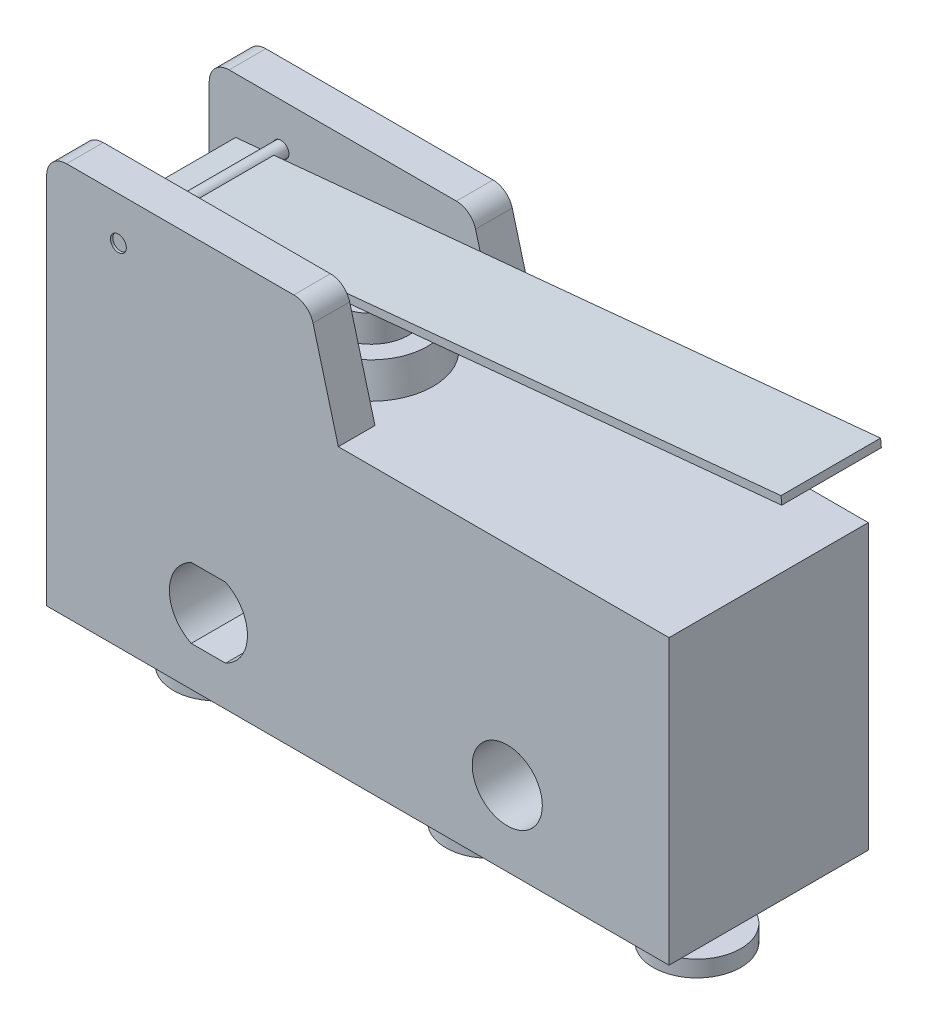
SolidWorks part; units mm, degrees
ref_plane "Front" through (0, 0, 0) normal (0, 0, 1) x (1, 0, 0)
ref_plane "Top" through (0, 0, 0) normal (0, 1, 0) x (1, 0, 0)
ref_plane "Right" through (0, 0, 0) normal (1, 0, 0) x (0, 0, -1)
sketch "Sketch1" plane through (0, 0, 0) normal (0, 0, 1) x (1, 0, 0)
  line L0 (-2.7559, 9.0424) -> (-2.7559, 0) construction
  line L1 (-9.9187, 0) -> (9.9187, 0)
  line L2 (-9.9187, 0) -> (-9.9187, 9.0424)
  line L3 (-9.9187, 9.0424) -> (9.9187, 9.0424)
  line L4 (9.9187, 0) -> (9.9187, 9.0424)
  line L5 (-5.3102, 3.5052) -> (-4.2148, 3.5052)
  line L6 (-5.3102, 1.27) -> (-4.2148, 1.27)
  line L7 (-4.7625, 2.3876) -> (4.7625, 2.3876) construction
  arc A0 (-5.3102, 3.5052) -> (-5.3102, 1.27) centre (-4.7625, 2.3876) ccw
  circle A1 centre (4.7625, 2.3876) radius 1.1176
  arc A2 (-4.2148, 1.27) -> (-4.2148, 3.5052) centre (-4.7625, 2.3876) ccw
  point P8 (-6.0071, 2.3876)
  point P15 (-3.5179, 2.3876)
  dimension "D3" = 2.4892
  dimension "D5" = 2.2352
  dimension "D6" = 5.1562
  dimension "D7" = 9.525
  dimension "D8" = 2.3876
  dimension "D9" = 7.5184
  dimension "D1" = 9.0424
  dimension "D2" = 19.8374
  dimension "D4" = 2.2352
extrude "Extrude1" add sketch "Sketch1" along normal mid plane 6.35
sketch "Sketch3" plane through (0, 0, 0) normal (0, 0, 1) x (1, 0, 0)
  line L0 (-4.7371, 9.0424) -> (-4.558, 10.0584)
  line L1 (-4.558, 10.0584) -> (-3.9497, 10.0584)
  line L2 (-3.9497, 10.0584) -> (-3.9497, 9.0424)
  line L3 (-3.9497, 9.0424) -> (-4.7371, 9.0424)
  line L4 (-3.9243, 9.5504) -> (-3.9243, 10.8966)
  line L5 (-2.7559, 9.0424) -> (-2.7559, 0) construction
  line L6 (-2.7559, 11.2776) -> (-2.7559, 9.5504)
  line L7 (-2.7559, 9.5504) -> (-3.9243, 9.5504)
  line L8 (-2.7559, 11.2776) -> (-2.7559, 11.5828) construction
  line L9 (-9.9187, 9.0424) -> (9.9187, 9.0424) construction
  line L10 (-3.9243, 10.8966) -> (-3.6191, 10.8966)
  arc A0 (-3.6191, 10.8966) -> (-2.7559, 11.2776) centre (-2.7559, 10.1092) cw
  circle A1 centre (4.7625, 2.3876) radius 1.1176 construction
  arc A2 (-5.3102, 3.5052) -> (-5.3102, 1.27) centre (-4.7625, 2.3876) ccw construction
  point P20 (-2.7559, 10.7696)
  dimension "D5" = 8.382
  dimension "D9" = 1.1684
  dimension "D1" = 3.9624
  dimension "D2" = 7.6708
  dimension "D3" = 2.3368
  dimension "D4" = 0.0254
  dimension "D6" = 0.508
  dimension "D7" = 80
  dimension "D8" = 0.381
  dimension "D10" = 0.508
revolve "Revolve1" add sketch "Sketch3" angle 360 about L8
sketch "Sketch5" plane through (0, 0, 0) normal (0, 0, 1) x (1, 0, 0)
  line L1 (-8.6487, 11.0236) -> (12.0015, 11.0236)
  line L2 (-8.6487, 11.0236) -> (-8.6487, 11.2776)
  line L3 (-8.6487, 11.2776) -> (12.0015, 11.2776)
  line L4 (12.0015, 11.0236) -> (12.0015, 11.2776)
  line L7 (-9.9187, 9.0424) -> (-0.6223, 9.0424) construction
  line L8 (-9.9187, 9.0424) -> (-9.9187, 12.5222) construction
  line L9 (-9.9187, 12.5222) -> (-0.6223, 12.5222) construction
  line L10 (-0.6223, 9.0424) -> (-0.6223, 12.5222) construction
  circle A1 centre (4.7625, 2.3876) radius 1.1176 construction
  arc A3 (-5.3102, 3.5052) -> (-5.3102, 1.27) centre (-4.7625, 2.3876) ccw construction
  dimension "D1" = 7.239
  dimension "D2" = 8.636
  dimension "D5" = 10.1346
  dimension "D6" = 9.2964
  dimension "D8" = 1.27
extrude "Extrude2" add sketch "Sketch5" along normal mid plane 3.175
sketch "Sketch6" plane through (0, 0, 3.175) normal (0, 0, 1) x (1, 0, 0)
  line L0 (-9.9187, 9.0424) -> (-9.9187, 11.8872)
  line L1 (-9.2837, 12.5222) -> (-2.042, 12.5222)
  line L2 (-1.4286, 12.0516) -> (-0.6223, 9.0424)
  line L3 (-0.6223, 9.0424) -> (-9.9187, 9.0424)
  line L4 (-9.9187, 9.0424) -> (-9.9187, 12.5222) construction
  line L5 (-9.9187, 12.5222) -> (-0.6223, 12.5222) construction
  line L6 (-9.9187, 9.0424) -> (9.9187, 9.0424) construction
  line L7 (-0.6223, 9.0424) -> (-0.6223, 12.5222) construction
  line L8 (-7.6327, 11.0236) -> (-7.6327, 11.2776) construction
  line L9 (-8.6487, 11.0236) -> (12.0015, 11.0236) construction
  line L10 (-8.6487, 11.2776) -> (12.0015, 11.2776) construction
  arc A0 (-9.9187, 11.8872) -> (-9.2837, 12.5222) centre (-9.2837, 11.8872) cw
  arc A1 (-2.042, 12.5222) -> (-1.4286, 12.0516) centre (-2.042, 11.8872) cw
  circle A2 centre (-7.6327, 11.1506) radius 0.254
  dimension "D2" = 0.635
  dimension "D3" = 2.286
  dimension "D4" = 0.508
  dimension "D1" = 15
extrude "Extrude3" add sketch "Sketch6" against normal blind 1.1684
mirror "Mirror1" about plane through (0, 0, 0) normal (0, 0, 1) of "Extrude3"
sketch "Sketch7" plane through (0, 0, 0) normal (0, 0, 1) x (1, 0, 0)
  circle A0 centre (-7.6327, 11.1506) radius 0.2413
  circle A1 centre (-7.6327, 11.1506) radius 0.254 construction
  dimension "D1" = 0.4826
extrude "Extrude4" add sketch "Sketch7" along normal mid plane 6.223
sketch "Sketch4" plane through (0, 0, 0) normal (0, 0, 1) x (1, 0, 0)
  line L0 (6.9977, -0.381) -> (6.9977, -1.5748)
  line L1 (6.9977, -1.5748) -> (6.2357, -1.5748)
  line L2 (6.2357, -1.5748) -> (6.2357, -2.0954)
  line L3 (6.2357, -2.0954) -> (6.6167, -2.3622)
  line L4 (6.6167, -2.3622) -> (7.6327, -2.3622)
  line L5 (7.6327, -2.3622) -> (7.6327, 0)
  line L6 (7.6327, 0) -> (6.6167, 0)
  line L7 (7.6327, 0) -> (7.6327, 1.016) construction
  line L8 (-9.9187, 0) -> (9.9187, 0) construction
  line L9 (9.9187, 0) -> (9.9187, 9.0424) construction
  arc A0 (6.6167, 0) -> (6.9977, -0.381) centre (6.6167, -0.381) cw
  arc A1 (-5.3102, 3.5052) -> (-5.3102, 1.27) centre (-4.7625, 2.3876) ccw construction
  dimension "D4" = 4.7498
  dimension "D1" = 1.27
  dimension "D2" = 2.794
  dimension "D3" = 1.5748
  dimension "D5" = 2.286
  dimension "D6" = 1.016
  dimension "D7" = 35
revolve "Revolve2" add sketch "Sketch4" angle 360 about L7
pattern_linear "LPattern1" count 2 spacing 6.604 along (-1, 0, 0) of "Revolve2"
pattern_linear "LPattern2" count 2 spacing 15.2908 along (-1, 0, 0) of "Revolve2"
move or copy body "Body-Move/Copy1" bodies to move or copy 118 copy no rotation origin (-7.6327, 11.1506, 0) rotation axis (0, 0, 1) rotation angle 5.5
sketch3d "3DSketch1"
  line L0 (-4.7625, 3.5052, 3.175) -> (-4.7625, 1.27, 3.175) construction
  line L1 (-4.2148, 3.5052, 3.175) -> (-5.3102, 3.5052, 3.175) construction
  line L2 (-5.3102, 1.27, 3.175) -> (-4.2148, 1.27, 3.175) construction
  circle A0 centre (-4.7625, 2.3876, 3.175) radius 0.4937 construction
  point P6 (-4.7625, 2.3876, 3.175)
  point P9 (-4.7625, 2.3876, 3.6687)
